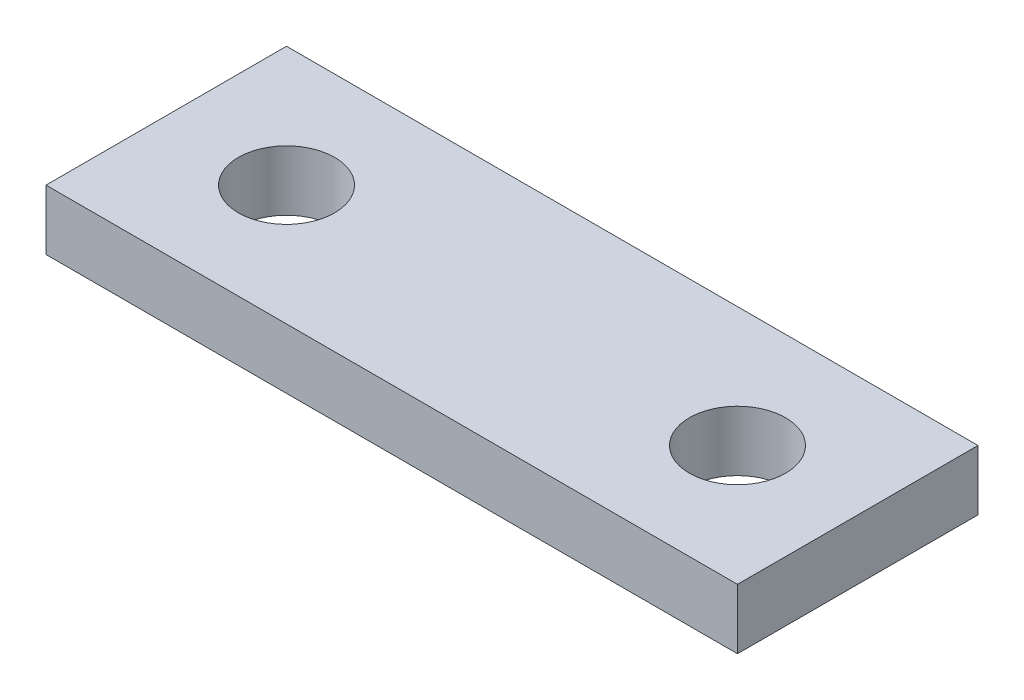
SolidWorks part; units mm, degrees
material "不锈钢 (铁素体)"
ref_plane "前视基准面" through (0, 0, 0) normal (0, 0, 1) x (1, 0, 0)
ref_plane "上视基准面" through (0, 0, 0) normal (0, 1, 0) x (1, 0, 0)
ref_plane "右视基准面" through (0, 0, 0) normal (1, 0, 0) x (0, 0, -1)
sketch "草图1" plane through (0, 0, 0) normal (0, 1, 0) x (1, 0, 0)
  line L1 (11.5, -4) -> (-11.5, -4)
  line L2 (11.5, -4) -> (11.5, 4)
  line L3 (11.5, 4) -> (-11.5, 4)
  line L4 (-11.5, -4) -> (-11.5, 4)
  line L5 (11.5, -4) -> (-11.5, 4) construction
  line L6 (11.5, 4) -> (-11.5, -4) construction
  point P0 (0, 0)
  dimension "D1" = 23
  dimension "D2" = 8
extrude "凸台-拉伸1" add sketch "草图1" along normal blind 2
sketch "草图2" plane through (0, 2, 0) normal (0, 1, 0) x (1, 0, 0)
  line L0 (-7.5, 0) -> (7.5, 0) construction
  circle A0 centre (-7.5, 0) radius 1.6
  circle A1 centre (7.5, 0) radius 1.6
  dimension "D1" = 3.2
  dimension "D3" = 15
extrude "切除-拉伸1" cut sketch "草图2" against normal through all
